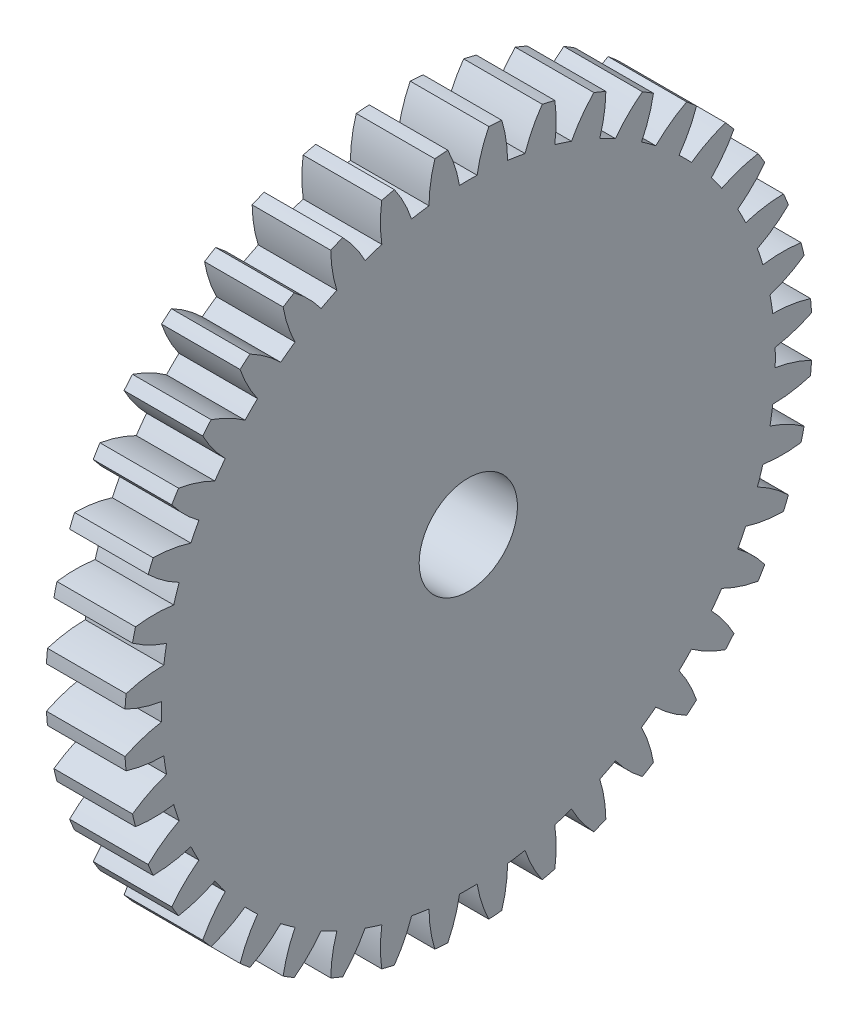
SolidWorks part; units mm, degrees
ref_plane "Plane1" through (0, 0, 0) normal (0, 0, 1) x (1, 0, 0)
ref_plane "Plane2" through (0, 0, 0) normal (0, 1, 0) x (1, 0, 0)
ref_plane "Plane3" through (0, 0, 0) normal (1, 0, 0) x (0, 0, -1)
other "Configuration Table"
sketch "HoldingSke" plane through (0, 0, 0) normal (0, 1, 0) x (1, 0, 0)
  line L0 (0, 0) -> (311.3205, -261.2289)
  line L1 (-15, 0) -> (100, 0) construction
  line L2 (0, 0) -> (-2.1039, 2.3779)
  line L3 (0, 0) -> (-11.863, 4.5341)
  line L4 (0, 0) -> (6.6156, 5.5511)
  line L5 (0, 0) -> (-47.5972, -17.7524)
  line L6 (0, 0) -> (-6.3167, -4.2619)
  line L7 (-2.1039, 2.3779) -> (8.8308, 51.9871)
  line L8 (-76.2, 54.61) -> (-65.4837, 54.61)
  line L9 (-67.7845, 28.3722) -> (-49.3413, 33.142)
  line L10 (-76.2, 71.12) -> (104.1128, 71.12)
  line L11 (0, 0) -> (-7.62, 0)
  line L12 (-76.2, 101.6) -> (-76.1428, 101.6)
  line L13 (24.9733, 27.94) -> (52.9518, 28.4284)
  line L14 (24.9733, 27.94) -> (24.9746, 27.94)
  line L15 (24.9733, 27.94) -> (100.4006, 29.5858)
  circle A0 centre (0, 0) radius 4.7625
  circle A1 centre (0, 0) radius 29.7644
  circle A2 centre (0, 0) radius 38.1
  circle A3 centre (0, 0) radius 4.7625
  dimension "MHD" = 59.5287
  dimension "Hub_dia" = 76.2
  dimension "Bore" = 9.525
  dimension "MBD" = 9.525
  dimension "Num_teeth" = 40
  dimension "Pitch" = 406.4
  dimension "Overall_len" = 50.8
  dimension "Show_teeth" = 40
  dimension "Thickness" = 7.62
  dimension "OAL" = 50.8001
  dimension "T_dim" = 10.7163
  dimension "Ap" = 14.5
  dimension "H" = 19.05
  dimension "Pitch_radius" = 180.3128
  dimension "Width" = 7.62
  dimension "Backlash" = 0.0571
  dimension "Addendum_fac" = 1
  dimension "Dedendum_fac" = 1.25
  dimension "Clearance_fac" = 0.25
  dimension "Dedendum_add" = 0.0013
sketch "BasProSke" plane through (0, 0, 0) normal (0, 1, 0) x (1, 0, 0)
  line L0 (-10, 0) -> (60, 0) construction
  line L1 (0, 0) -> (0, 33.3375)
  line L2 (0, 0) -> (7.62, 0)
  line L3 (7.62, 0) -> (7.62, 33.3375)
  line L4 (7.62, 33.3375) -> (0, 33.3375)
  dimension "Thickness" = 7.62
  dimension "Diameter" = 66.675
revolve "Base-Revolve" add sketch "BasProSke" angle 360 about L0
sketch "TooCutSke" plane through (0, 0, 0) normal (1, 0, 0) x (0, 0, -1)
  line L1 (0, 0) -> (0, 107) construction
  line L2 (0, 0) -> (-1.3465, 31.7214) construction
  line L3 (0, 0) -> (-4.9789, 63.263) construction
  line L4 (-1.3465, 31.7214) -> (-2.4895, 31.6315) construction
  arc A0 (0.8551, 29.7521) -> (-0.8551, 29.7521) centre (0, 0) ccw
  arc A1 (2.0001, 33.3029) -> (-2.0001, 33.3029) centre (0, 0) ccw
  circle A2 centre (0, 0) radius 31.75 construction
  circle A3 centre (0, 0) radius 30.7387 construction
  arc A4 (-0.8551, 29.7521) -> (-2.0001, 33.3029) centre (-13.3836, 27.6721) ccw
  arc A5 (2.0001, 33.3029) -> (0.8551, 29.7521) centre (13.3836, 27.6721) ccw
  dimension "Root_dia" = 59.5287
  dimension "Overcut_dia" = 66.7258
  dimension "Pitch_dia" = 63.5
  dimension "Base_dia" = 61.4774
  dimension "Flank_rad" = 12.7
  dimension "Half_ang" = 4.5
  dimension "Half_CT" = 1.1465
extrude "ToothCut" cut sketch "TooCutSke" along normal through all
fillet "Breaks" [suppressed] radius 0.0318
fillet "RootFillets" [suppressed] radius 0.3981
pattern_circular "TeethCuts" count 40 every 9 about axis through (-10, 0, 0) along (1, 0, 0) of "ToothCut", "RootFillets", "Breaks"
sketch "HubNeaOneSke" plane through (0, 0, 0) normal (-1, 0, 0) x (0, 0, 1)
  circle A0 centre (0, 0) radius 29.7644
  dimension "Diameter" = 59.5287
extrude "HubNearOne" [suppressed] add sketch "HubNeaOneSke" along normal blind 43.1801
sketch "HubNeaBotSke" plane through (0, 0, 0) normal (-1, 0, 0) x (0, 0, 1)
  circle A0 centre (0, 0) radius 29.7644
  dimension "Diameter" = 59.5287
extrude "HubNearBoth" [suppressed] add sketch "HubNeaBotSke" along normal blind 21.59
ref_plane "FarPln" through (7.62, 0, 0) normal (1, 0, 0) x (0, 0, -1)
sketch "HubFarSke" plane through (7.62, 0, 0) normal (1, 0, 0) x (0, 0, -1)
  circle A0 centre (0, 0) radius 29.7644
  dimension "Diameter" = 59.5287
extrude "HubFar" [suppressed] add sketch "HubFarSke" along normal blind 21.59
sketch "BorSke" plane through (0, 0, 0) normal (1, 0, 0) x (0, 0, -1)
  circle A0 centre (0, 0) radius 4.7625
  dimension "Diameter" = 9.525
extrude "Bore" cut sketch "BorSke" along normal mid plane 101.6001
sketch "KeySke" plane through (0, 0, 0) normal (1, 0, 0) x (0, 0, -1)
  line L0 (-1.1913, 0) -> (-1.1913, 5.9538)
  line L1 (-1.1913, 5.9538) -> (1.1913, 5.9538)
  line L2 (1.1913, 5.9538) -> (1.1913, 0)
  line L3 (0, 0) -> (0, 34) construction
  line L4 (-1.1913, 0) -> (1.1913, 0)
  dimension "Offset" = 5.9538
  dimension "Width" = 2.3825
extrude "Keyway" [suppressed] cut sketch "KeySke" along normal mid plane 101.6001
pattern_circular "Keyway2" [suppressed] count 2 every 90 about axis through (-10, 0, 0) along (1, 0, 0)
equation "' \"Pitch@HoldingSke\" = 4"
equation "' \"Num_teeth@HoldingSke\" = 12"
equation "' \"Ap@HoldingSke\" =  20"
equation "' \"Ap@HoldingSke\" = 20"
equation "' \"Width@HoldingSke\" = 0.5"
equation "' \"Hub_dia@HoldingSke\"= 1"
equation "' \"Hub_dia@HoldingSke\" = 1"
equation "' \"Overall_len@HoldingSke\" = 1.0"
equation "' \"Bore@HoldingSke\" = 0.75"
equation "' \"T_dim@HoldingSke\" = 0.85"
equation "' \"Width@KeySke\" = 0.25"
equation "' \"Show_teeth@HoldingSke\" = 13"
equation "' \"Backlash@HoldingSke\" = 0.009"
equation "' \"Addendum_fac@HoldingSke\" = 1.0"
equation "' \"Dedendum_fac@HoldingSke\" = 1.25"
equation "' \"Dedendum_add@HoldingSke\" = 0.00005"
equation "' \"Clearance_fac@HoldingSke\" = 0.25"
equation "' \"Pitch@HoldingSke\" = 0.5"
equation "' \"Num_teeth@HoldingSke\" = 23"
equation "' \"Show_teeth@HoldingSke\" = 23"
equation "' \"Backlash@HoldingSke\" = 0.0375"
equation "\"Overcut_dia@TooCutSke\" = (\"Num_teeth@HoldingSke\" + 2 * \"Addendum_fac@HoldingSke\") / \"Pitch@HoldingSke\" + 0.002"
equation "\"Pitch_dia@TooCutSke\" = \"Num_teeth@HoldingSke\" / \"Pitch@HoldingSke\""
equation "\"Base_dia@TooCutSke\" = \"Num_teeth@HoldingSke\" / \"Pitch@HoldingSke\" * cos((\"Ap@HoldingSke\"  * 3.14159265 / 180))"
equation "\"Root_dia@TooCutSke\" = (\"Num_teeth@HoldingSke\" + 2) / \"Pitch@HoldingSke\" - 2 * (\"Addendum_fac@HoldingSke\" + \"Dedendum_fac@HoldingSke\") / \"Pitch@HoldingSke\" - \"Dedendum_add@HoldingSke\" * 2"
equation "\"Half_ang@TooCutSke\" = 180 / \"Num_teeth@HoldingSke\""
equation "\"Half_CT@TooCutSke\" = \"Num_teeth@HoldingSke\" / \"Pitch@HoldingSke\" * sin((3.14159265 / 2 / \"Num_teeth@HoldingSke\")) / 2 - 7 * \"Backlash@HoldingSke\" / 4"
equation "\"Flank_rad@TooCutSke\" = \"Num_teeth@HoldingSke\" / \"Pitch@HoldingSke\" / 5"
equation "\"Radius@RootFillets\" = \"Clearance_fac@HoldingSke\" / \"Pitch@HoldingSke\" + \"Dedendum_add@HoldingSke\""
equation "\"Break_rad@Breaks\" = 0.02 / \"Pitch@HoldingSke\""
equation "\"Thickness@HoldingSke\" = \"Width@HoldingSke\""
equation "\"OAL@HoldingSke\" = \"Thickness@HoldingSke\""
equation "\"MHD@HoldingSke\" = (\"Num_teeth@HoldingSke\" + 2) / \"Pitch@HoldingSke\" - 2 * (\"Addendum_fac@HoldingSke\" + \"Dedendum_fac@HoldingSke\")  / \"Pitch@HoldingSke\" - \"Dedendum_add@HoldingSke\" * 2"
equation "\"MBD@HoldingSke\" = (\"Num_teeth@HoldingSke\" + 2) / \"Pitch@HoldingSke\" - 2 * (\"Addendum_fac@HoldingSke\" + \"Dedendum_fac@HoldingSke\")  / \"Pitch@HoldingSke\" - \"Dedendum_add@HoldingSke\" * 2 - 0.002"
equation "\"MHD@HoldingSke\" = ((sgn( \"MHD@HoldingSke\" - \"Hub_dia@HoldingSke\" )-1)*( \"MHD@HoldingSke\" - \"Hub_dia@HoldingSke\" ))/-2+ \"Hub_dia@HoldingSke\""
equation "\"MBD@HoldingSke\" = ((sgn( \"MBD@HoldingSke\" - \"Bore@HoldingSke\" )-1)*( \"MBD@HoldingSke\" - \"Bore@HoldingSke\" ))/-2+ \"Bore@HoldingSke\""
equation "\"OAL@HoldingSke\" = ((sgn( \"OAL@HoldingSke\" - \"Overall_len@HoldingSke\" )+1)*( \"OAL@HoldingSke\" - \"Overall_len@HoldingSke\" ))/2 + \"Overall_len@HoldingSke\" + 0.000002"
equation "\"Num_teeth@TeethCuts\" = int( \"Show_teeth@HoldingSke\" ) + 1"
equation "\"Num_teeth@TeethCuts\" = ((sgn( \"Num_teeth@TeethCuts\" - \"Num_teeth@HoldingSke\" )-1)*( \"Num_teeth@TeethCuts\" - \"Num_teeth@HoldingSke\" ))/-2+ \"Num_teeth@HoldingSke\""
equation "\"Num_teeth@TeethCuts\" = ((sgn( \"Num_teeth@TeethCuts\" - 2.0)+1)*( \"Num_teeth@TeethCuts\" - 2.0))/2 +2.0"
equation "\"Angle@TeethCuts\" = 360.0 / \"Num_teeth@HoldingSke\""
equation "\"Diameter@BasProSke\" = (\"Num_teeth@HoldingSke\" + 2 * \"Addendum_fac@HoldingSke\") / \"Pitch@HoldingSke\""
equation "\"Thickness@BasProSke\"  = \"Thickness@HoldingSke\""
equation "' \"Fillet_rad@BasProSke\" =  \"Thickness@HoldingSke\" * 0.05"
equation "' \"Fillet_rad@BasProSke\" = \"Thickness@HoldingSke\" * 0.05"
equation "\"MHD@HoldingSke\" = ((sgn( \"MHD@HoldingSke\" - \"Root_dia@TooCutSke\" )-1)*( \"MHD@HoldingSke\" - \"Root_dia@TooCutSke\" ))/-2+ \"Root_dia@TooCutSke\""
equation "\"Diameter@HubNeaOneSke\" = \"MHD@HoldingSke\""
equation "\"Length@HubNearOne\" = \"OAL@HoldingSke\" - \"Thickness@BasProSke\""
equation "\"Diameter@HubNeaBotSke\" = \"MHD@HoldingSke\""
equation "\"Length@HubNearBoth\" = ( \"OAL@HoldingSke\" - \"Thickness@BasProSke\" ) / 2.0"
equation "\"Thickness@FarPln\" = \"Thickness@BasProSke\""
equation "\"Diameter@HubFarSke\" = \"MHD@HoldingSke\""
equation "\"Length@HubFar\" = ( \"OAL@HoldingSke\" - \"Thickness@BasProSke\" ) / 2.0"
equation "\"D1@Bore\" = \"OAL@HoldingSke\" * 2.0"
equation "\"D1@Keyway\" = \"OAL@HoldingSke\" * 2.0"
equation "\"Offset@KeySke\" = \"T_dim@HoldingSke\" - \"MBD@HoldingSke\" / 2.0"
